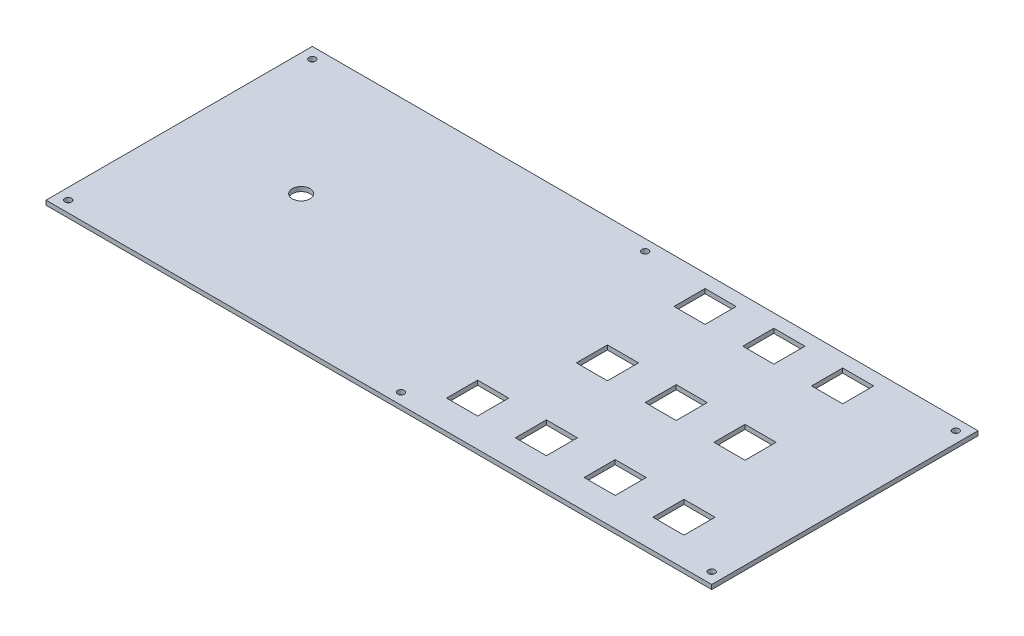
SolidWorks part; units mm, degrees
ref_plane "Front" through (0, 0, 0) normal (0, 0, 1) x (1, 0, 0)
ref_plane "Top" through (0, 0, 0) normal (0, 1, 0) x (1, 0, 0)
ref_plane "Right" through (0, 0, 0) normal (1, 0, 0) x (0, 0, -1)
sketch "Sketch1" plane through (0, 0, 0) normal (0, 1, 0) x (1, 0, 0)
  line L0 (17.5, -33) -> (31.5, -33)
  line L1 (-150, 60) -> (150, 60)
  line L2 (-150, 60) -> (-150, -60)
  line L3 (-150, -60) -> (150, -60)
  line L4 (150, 60) -> (150, -60)
  line L5 (-150, 60) -> (150, -60) construction
  line L6 (-150, -60) -> (150, 60) construction
  line L7 (33, 10) -> (47, 10)
  line L8 (33, 10) -> (33, -4)
  line L9 (33, -4) -> (47, -4)
  line L10 (47, 10) -> (47, -4)
  line L11 (33, 10) -> (47, -4) construction
  line L12 (33, -4) -> (47, 10) construction
  line L13 (30.5, 19.5) -> (49.5, 19.5) construction
  line L14 (30.5, 19.5) -> (30.5, -13.5) construction
  line L15 (30.5, -13.5) -> (49.5, -13.5) construction
  line L16 (49.5, 19.5) -> (49.5, -13.5) construction
  line L17 (30.5, 19.5) -> (49.5, -13.5) construction
  line L18 (30.5, -13.5) -> (49.5, 19.5) construction
  line L19 (17.5, -33) -> (17.5, -47)
  line L20 (17.5, -47) -> (31.5, -47)
  line L21 (31.5, -33) -> (31.5, -47)
  line L22 (17.5, -33) -> (31.5, -47) construction
  line L23 (17.5, -47) -> (31.5, -33) construction
  line L24 (15, -23.5) -> (34, -23.5) construction
  line L25 (15, -23.5) -> (15, -56.5) construction
  line L26 (15, -56.5) -> (34, -56.5) construction
  line L27 (34, -23.5) -> (34, -56.5) construction
  line L28 (15, -23.5) -> (34, -56.5) construction
  line L29 (15, -56.5) -> (34, -23.5) construction
  line L30 (64, 10) -> (64, -4)
  line L31 (64, 10) -> (78, 10)
  line L32 (78, 10) -> (78, -4)
  line L33 (64, -4) -> (78, -4)
  line L34 (95, 10) -> (95, -4)
  line L35 (95, 10) -> (109, 10)
  line L36 (109, 10) -> (109, -4)
  line L37 (95, -4) -> (109, -4)
  line L38 (48.5, -33) -> (62.5, -33)
  line L39 (62.5, -33) -> (62.5, -47)
  line L40 (48.5, -47) -> (62.5, -47)
  line L41 (48.5, -33) -> (48.5, -47)
  line L42 (79.5, -33) -> (93.5, -33)
  line L43 (93.5, -33) -> (93.5, -47)
  line L44 (79.5, -47) -> (93.5, -47)
  line L45 (79.5, -33) -> (79.5, -47)
  line L46 (110.5, -33) -> (124.5, -33)
  line L47 (124.5, -33) -> (124.5, -47)
  line L48 (110.5, -47) -> (124.5, -47)
  line L49 (110.5, -33) -> (110.5, -47)
  line L50 (31.5, -47) -> (48.5, -47) construction
  line L51 (33, 54) -> (47, 54)
  line L52 (33, 54) -> (33, 40)
  line L53 (33, 40) -> (47, 40)
  line L54 (47, 54) -> (47, 40)
  line L55 (33, 54) -> (47, 40) construction
  line L56 (33, 40) -> (47, 54) construction
  line L57 (23.5, 56.5) -> (56.5, 56.5) construction
  line L58 (23.5, 56.5) -> (23.5, 37.5) construction
  line L59 (23.5, 37.5) -> (56.5, 37.5) construction
  line L60 (56.5, 56.5) -> (56.5, 37.5) construction
  line L61 (23.5, 56.5) -> (56.5, 37.5) construction
  line L62 (23.5, 37.5) -> (56.5, 56.5) construction
  line L63 (64, 54) -> (64, 40)
  line L64 (64, 54) -> (78, 54)
  line L65 (78, 54) -> (78, 40)
  line L66 (64, 40) -> (78, 40)
  line L67 (95, 54) -> (95, 40)
  line L68 (95, 54) -> (109, 54)
  line L69 (109, 54) -> (109, 40)
  line L70 (95, 40) -> (109, 40)
  line L71 (-45, 0) -> (-45, -60) construction
  line L72 (0, 0) -> (0, 35.0503) construction
  line L73 (0, 0) -> (-35.7443, 0) construction
  line L74 (0, 60) -> (0, -60) construction
  circle A0 centre (-95, 0) radius 50 construction
  circle A1 centre (-95, 0) radius 4
  circle A2 centre (-145, 55) radius 1.5
  circle A3 centre (145, 55) radius 1.5
  circle A4 centre (-145, -55) radius 1.5
  circle A5 centre (145, -55) radius 1.5
  circle A6 centre (5, 55) radius 1.5
  circle A7 centre (5, -55) radius 1.5
  point P0 (0, 0)
  point P6 (40, 3)
  point P11 (40, 3)
  point P17 (24.5, -40)
  point P22 (24.5, -40)
  point P48 (40, 47)
  point P49 (-150, 0)
  point P51 (40, 47)
  point P59 (40, -47)
  dimension "D21" = 100
  dimension "D26" = 8
  dimension "D29" = 3
  dimension "D1" = 300
  dimension "D2" = 120
  dimension "D3" = 33
  dimension "D4" = 19
  dimension "D5" = 14
  dimension "D6" = 33
  dimension "D7" = 19
  dimension "D8" = 14
  dimension "D9" = 43
  dimension "D10" = 15.5
  dimension "D12" = 4
  dimension "D13" = 31
  dimension "D14" = 31
  dimension "D15" = 33
  dimension "D16" = 19
  dimension "D17" = 14
  dimension "D18" = 3
  dimension "D19" = 55
  dimension "D20" = 31
  dimension "D22" = 18
  dimension "D23" = 3.5
  dimension "D24" = 3.5
  dimension "D25" = 60
  dimension "D27" = 5
  dimension "D28" = 5
  dimension "D31" = 5
  dimension "D11" = 3
  dimension "D30" = 2
extrude "Boss-Extrude1" add sketch "Sketch1" along normal blind 2
